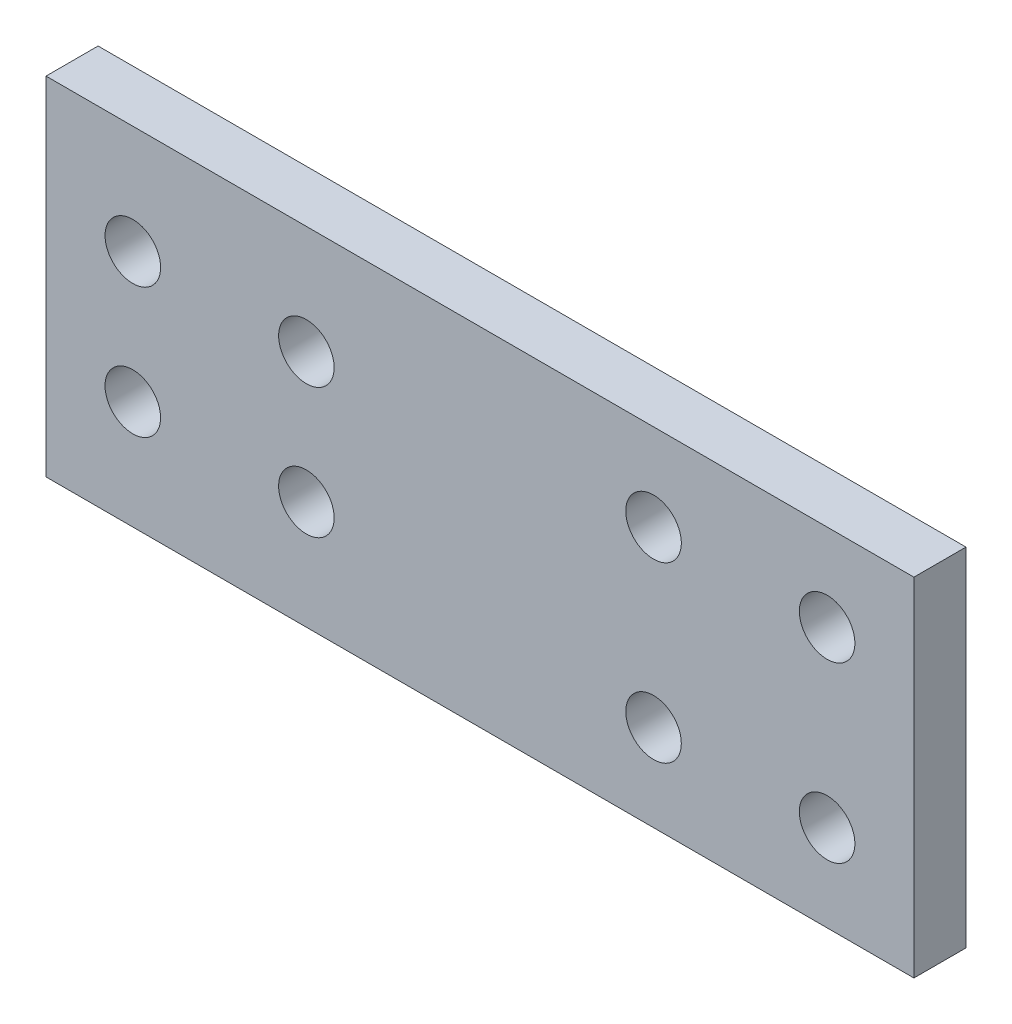
SolidWorks part; units mm, degrees
ref_plane "前视基准面" through (0, 0, 0) normal (0, 0, 1) x (1, 0, 0)
ref_plane "上视基准面" through (0, 0, 0) normal (0, 1, 0) x (1, 0, 0)
ref_plane "右视基准面" through (0, 0, 0) normal (1, 0, 0) x (0, 0, -1)
other "Configuration Table"
sketch "草图1" plane through (0, 0, 0) normal (0, 0, 1) x (1, 0, 0)
  line L0 (40, 0) -> (40, -20) construction
  line L1 (0, 0) -> (50, 0)
  line L2 (0, 0) -> (0, -20)
  line L3 (0, -20) -> (50, -20)
  line L4 (50, 0) -> (50, -20)
  line L5 (50, -10) -> (40, -10) construction
  line L6 (10, 0) -> (10, -20) construction
  circle A0 centre (45, -5) radius 1.6
  circle A1 centre (45, -15) radius 1.6
  circle A2 centre (35, -15) radius 1.6
  circle A3 centre (35, -5) radius 1.6
  circle A4 centre (5, -6.25) radius 1.6
  circle A5 centre (5, -13.75) radius 1.6
  circle A6 centre (15, -13.75) radius 1.6
  circle A7 centre (15, -6.25) radius 1.6
  dimension "D4" = 3.2
  dimension "D7" = 3.2
  dimension "D1" = 20
  dimension "D2" = 50
  dimension "D3" = 10
  dimension "D5" = 5
  dimension "D6" = 5
  dimension "D8" = 3.75
  dimension "D9" = 5
  dimension "D10" = 30
extrude "凸台-拉伸1" add sketch "草图1" along normal blind 3
